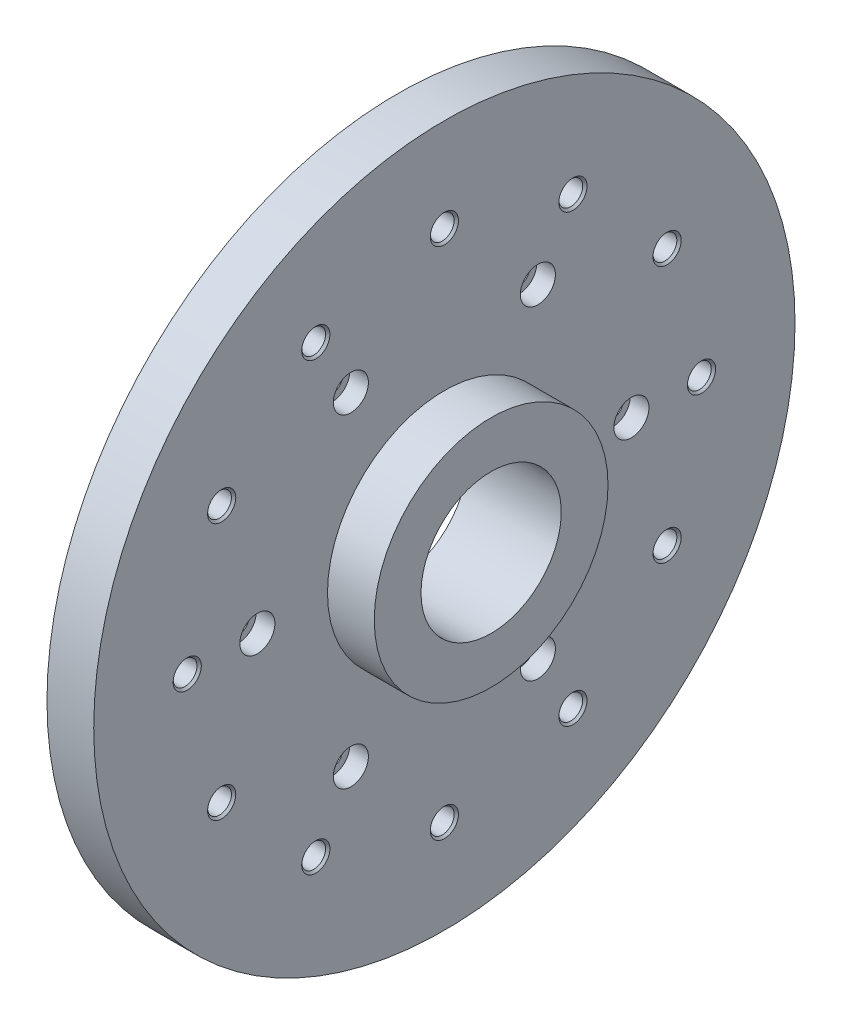
SolidWorks part; units mm, degrees
ref_plane "Ön Düzlem" through (0, 0, 0) normal (0, 0, 1) x (1, 0, 0)
ref_plane "Üst Düzlem" through (0, 0, 0) normal (0, 1, 0) x (1, 0, 0)
ref_plane "Sağ Düzlem" through (0, 0, 0) normal (1, 0, 0) x (0, 0, -1)
sketch "Çizim1" plane through (0, 0, 0) normal (0, 0, 1) x (1, 0, 0)
  line L0 (-47.5835, 30) -> (-7.5835, 30)
  line L1 (-7.5835, 30) -> (-7.5835, 50)
  line L2 (-7.5835, 50) -> (-27.5835, 50)
  line L3 (-27.5835, 50) -> (-27.5835, 150)
  line L4 (-27.5835, 150) -> (-47.5835, 150)
  line L5 (-47.5835, 150) -> (-47.5835, 30)
  line L6 (-58.3479, 0) -> (88.9293, 0) construction
  dimension "D1" = 150
  dimension "D2" = 40
  dimension "D3" = 50
  dimension "D4" = 30
  dimension "D5" = 20
revolve "Döndür1" add sketch "Çizim1" angle 360 about L6
hole_wizard "M8 SHCS İçin Havşa1" positions "Çizim4" profile "Çizim5" counterbore size "M8" standard "ANSI Metrik" end condition through all
sketch "Çizim4" plane through (-27.5835, 0, 0) normal (1, 0, 0) x (0, 0, -1)
  point P0 (80, 0)
  point P2 (401.2887, 148.9814)
  point P8 (40, -69.282)
  point P9 (-40, -69.282)
  point P10 (-80, 0)
  point P11 (-40, 69.282)
  point P12 (40, 69.282)
  point P13 (0, 0)
  dimension "D1" = 80
  dimension "D2" = 6
sketch "Çizim5" plane through (-27.5835, 0, -80) normal (0, 1, 0) x (0, 0, -1)
  line L0 (0, 0) -> (0, 20)
  line L1 (0, 20) -> (4.5, 20)
  line L3 (4.5, 20) -> (4.5, 8)
  line L4 (4.5, 8) -> (7.5, 8)
  line L5 (7.5, 8) -> (7.5, 0)
  line L7 (7.5, 0) -> (0, 0)
  line L11 (0, -6.35) -> (0, 107.95) construction
  dimension "Thru Hole Dia." = 9
  dimension "Thru Hole Depth" = 20
  dimension "C'Bore Dia." = 15
  dimension "C'Bore Depth" = 8
hole_wizard "M12x1.75 Dişli Delik1" positions "Çizim6" profile "Çizim7" tap size "M12x1.75" standard "ANSI Metrik" end condition through all
sketch "Çizim6" plane through (-27.5835, 0, 0) normal (1, 0, 0) x (0, 0, -1)
  point P0 (110, 0)
  point P8 (95.2628, -55)
  point P9 (55, -95.2628)
  point P10 (0, -110)
  point P11 (-55, -95.2628)
  point P12 (-95.2628, -55)
  point P13 (-110, 0)
  point P14 (-95.2628, 55)
  point P15 (-55, 95.2628)
  point P16 (0, 110)
  point P17 (55, 95.2628)
  point P18 (95.2628, 55)
  point P19 (0, 0)
  dimension "D1" = 110
  dimension "D2" = 12
sketch "Çizim7" plane through (-27.5835, 0, -110) normal (0, 1, 0) x (0, 0, -1)
  line L0 (0, 0) -> (0, 20)
  line L1 (0, 20) -> (5.1, 20)
  line L2 (5.1, 20) -> (5.1, 0.925)
  line L3 (5.1, 0.925) -> (6.025, 0)
  line L5 (6.025, 0) -> (0, 0)
  line L6 (-5.1, 0.925) -> (-6.025, 0) construction
  line L11 (0, -6.35) -> (0, 107.95) construction
  dimension "Thru Tap Drill Dia." = 10.2
  dimension "Thru Tap Drill Depth" = 20
  dimension "Near C'Sink Dia." = 12.05
  dimension "Near C'Sink Angle" = 90
cosmetic thread "Delik Dişi1" parameters "D2"=12
cosmetic thread "Delik Dişi2" parameters "D2"=12
cosmetic thread "Delik Dişi3" parameters "D2"=12
cosmetic thread "Delik Dişi4" parameters "D2"=12
cosmetic thread "Delik Dişi5" parameters "D2"=12
cosmetic thread "Delik Dişi6" parameters "D2"=12
cosmetic thread "Delik Dişi7" parameters "D2"=12
cosmetic thread "Delik Dişi8" parameters "D2"=12
cosmetic thread "Delik Dişi9" parameters "D2"=12
cosmetic thread "Delik Dişi10" parameters "D2"=12
cosmetic thread "Delik Dişi11" parameters "D2"=12
cosmetic thread "Delik Dişi12" parameters "D2"=12
